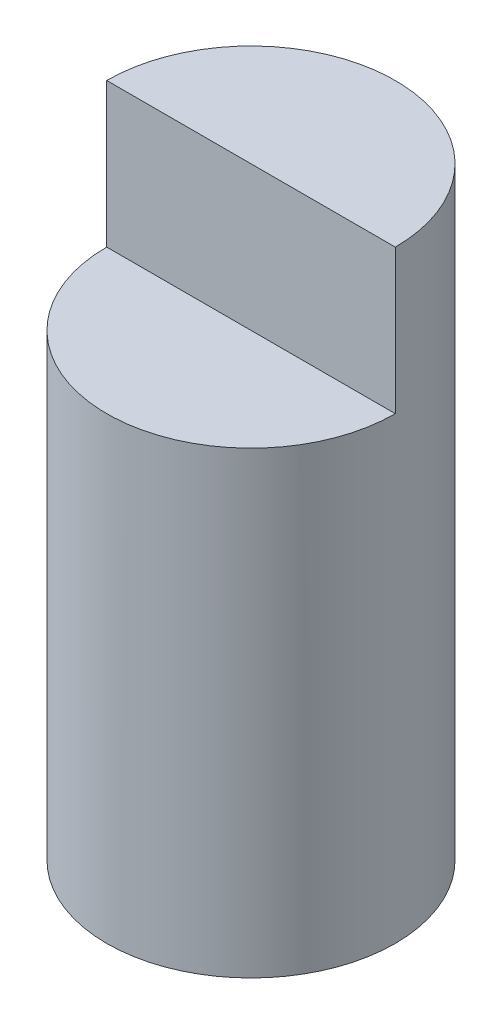
SolidWorks part; units mm, degrees
ref_plane "Front Plane" through (0, 0, 0) normal (0, 0, 1) x (1, 0, 0)
ref_plane "Top Plane" through (0, 0, 0) normal (0, 1, 0) x (1, 0, 0)
ref_plane "Right Plane" through (0, 0, 0) normal (1, 0, 0) x (0, 0, -1)
sketch "Sketch1" plane through (0, 0, 0) normal (0, 1, 0) x (1, 0, 0)
  circle A0 centre (25.0404, 11.3573) radius 3.175
  dimension "D1" = 6.35
extrude "Boss-Extrude1" add sketch "Sketch1" along normal offset from surface (13.2715 mm away) 0.254
sketch "Sketch2" plane through (0, 13.2715, 0) normal (0, 1, 0) x (1, 0, 0)
  line L1 (28.2154, 6.823) -> (21.8654, 6.823)
  line L2 (28.2154, 6.823) -> (28.2154, 11.3573)
  line L3 (28.2154, 11.3573) -> (21.8654, 11.3573)
  line L4 (21.8654, 6.823) -> (21.8654, 11.3573)
  circle A0 centre (25.0404, 11.3573) radius 3.175 construction
extrude "clear LCD fastener" cut sketch "Sketch2" against normal blind 3.175
sketch "Sketch3" plane through (0, 0, 0) normal (0, -1, 0) x (1, 0, 0)
  circle A0 centre (25.0404, -11.3573) radius 1.27
  circle A1 centre (25.0404, -11.3573) radius 3.175 construction
  dimension "D1" = 2.54
extrude "tap number 4" cut sketch "Sketch3" against normal offset from surface (8.509 mm away) 1.5875 up to face at (25.0404, 10.0965, -9.7698)
